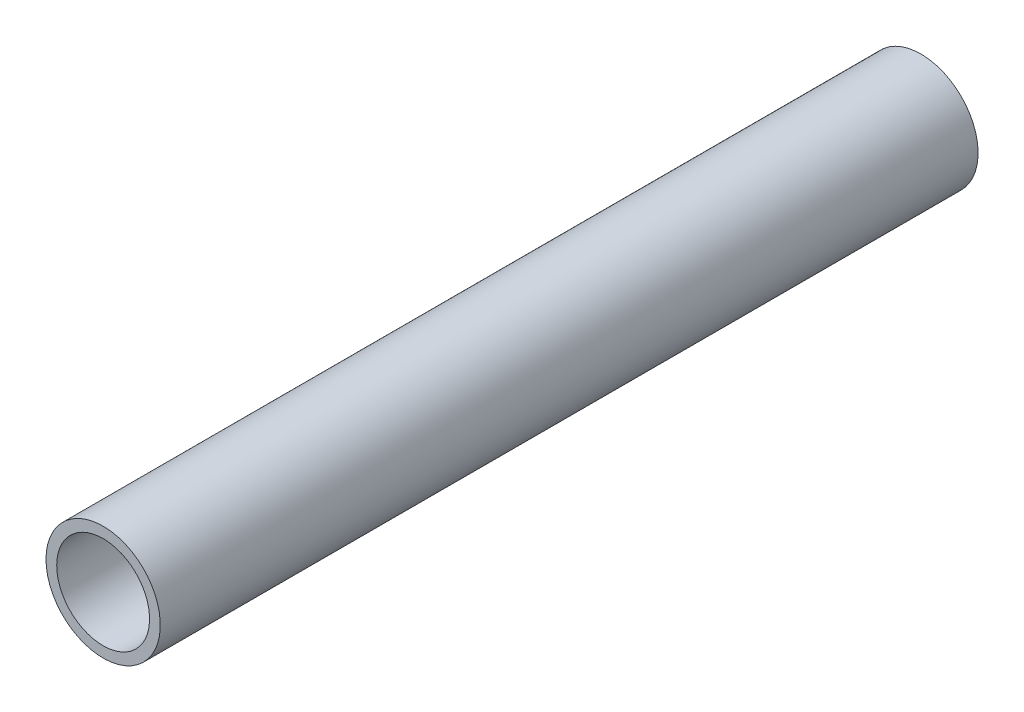
SolidWorks part; units mm, degrees
ref_plane "Alzado" through (0, 0, 0) normal (0, 0, 1) x (1, 0, 0)
ref_plane "Planta" through (0, 0, 0) normal (0, 1, 0) x (1, 0, 0)
ref_plane "Vista lateral" through (0, 0, 0) normal (1, 0, 0) x (0, 0, -1)
sketch "Croquis1" plane through (0, 0, 0) normal (0, 0, 1) x (1, 0, 0)
  circle A0 centre (0, 0) radius 16
  dimension "D1" = 32
extrude "Extruir1" add sketch "Croquis1" along normal mid plane 229
shell "Vaciado1" thickness 3
